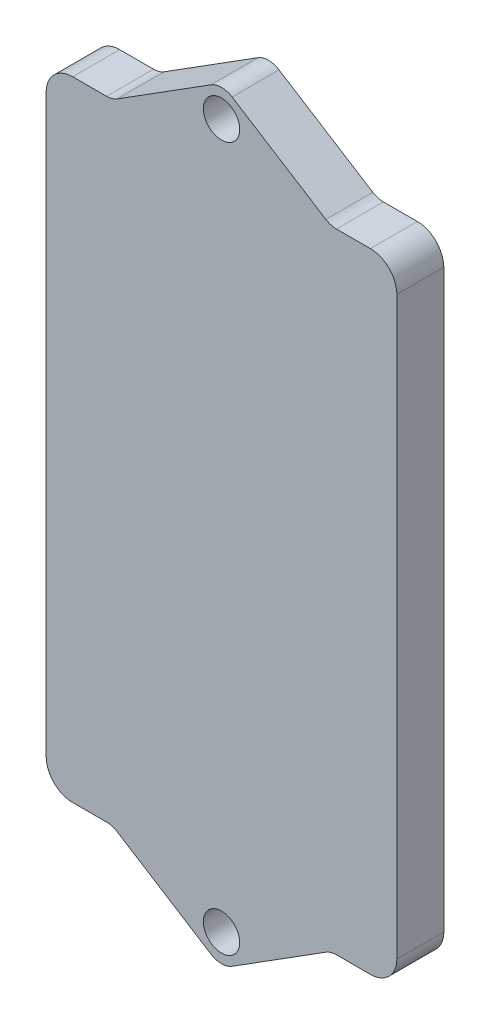
SolidWorks part; units mm, degrees
ref_plane "Plan de face" through (0, 0, 0) normal (0, 0, 1) x (1, 0, 0)
ref_plane "Plan de dessus" through (0, 0, 0) normal (0, 1, 0) x (1, 0, 0)
ref_plane "Plan de droite" through (0, 0, 0) normal (1, 0, 0) x (0, 0, -1)
sketch "Esquisse1" plane through (0, 0, 0) normal (0, 0, 1) x (1, 0, 0)
  line L0 (10, 95) -> (26.5, 105.4)
  line L1 (0, 0) -> (10, 0)
  line L2 (0, 0) -> (0, 95)
  line L3 (0, 95) -> (10, 95)
  line L4 (53, 0) -> (53, 95)
  line L5 (26.5, 105.4) -> (43, 95)
  line L7 (10, 0) -> (26.5, -10.4)
  line L8 (26.5, -10.4) -> (43, 0)
  line L9 (43, 95) -> (53, 95)
  line L10 (43, 0) -> (53, 0)
  circle A0 centre (26.5, 100.71) radius 2.75
  circle A1 centre (26.5, -5.71) radius 2.75
  point P16 (5, 0)
  dimension "D9" = 5.5
  dimension "D10" = 5.5
  dimension "D1" = 53
  dimension "D2" = 95
  dimension "D3" = 10
  dimension "D4" = 10
  dimension "D5" = 10.4
  dimension "D6" = 10.4
  dimension "D7" = 26.5
  dimension "D8" = 26.5
  dimension "D11" = 5.71
  dimension "D12" = 5.71
extrude "Boss.-Extru.1" add sketch "Esquisse1" along normal blind 7.1
fillet "Congé1" radius 3 6 edges at (43, 0, 3.55) (10, 0, 3.55) (10, 95, 3.55) (43, 95, 3.55) (26.5, -10.4, 3.55) (26.5, 105.4, 3.55)
fillet "Congé2" radius 4 4 edges at (0, 95, 3.55) (53, 95, 3.55) (53, 0, 3.55) (0, 0, 3.55)
sketch "Esquisse2" plane through (0, 0, 7.1) normal (0, 0, 1) x (1, 0, 0)
  line L0 (26.5, -8.46) -> (26.5, 103.46) construction
  circle A0 centre (26.5, -5.71) radius 2.75 construction
  circle A1 centre (26.5, 100.71) radius 2.75 construction
sketch "Esquisse3" plane through (0, 0, 0) normal (0, -1, 0) x (1, 0, 0)
  line L0 (5.1547, 0) -> (4, 2)
  line L1 (4, 0) -> (9.1334, 0) construction
  line L3 (10.1455, 2.0625) -> (8.9547, 0)
  line L4 (8.9547, 0) -> (5.1547, 0)
  line L5 (44.0092, 0) -> (42.8545, 2)
  line L6 (43.8666, 0) -> (49, 0) construction
  line L8 (49, 2.0625) -> (47.8092, 0)
  line L9 (47.8092, 0) -> (44.0092, 0)
  line L10 (4, 7.1) -> (4, 0) construction
  line L12 (4, 2) -> (4, 2.6625)
  line L13 (4, 2.6625) -> (10.1455, 2.6625)
  line L14 (10.1455, 2.0625) -> (10.1455, 2.6625)
  line L16 (42.8545, 2) -> (42.8545, 2.6625)
  line L17 (42.8545, 2.6625) -> (49, 2.6625)
  line L18 (49, 2.0625) -> (49, 2.6625)
  line L19 (49, 0) -> (49, 7.1) construction
  dimension "D1" = 60
  dimension "D2" = 60
  dimension "D3" = 3.8
  dimension "D4" = 3.8
  dimension "D5" = 2
  dimension "D6" = 2
  dimension "D7" = 0.6
  dimension "D8" = 0.6
extrude "Enlèv. mat.-Extru.1" cut sketch "Esquisse3" against normal blind 78 and the other way through all
fillet "Congé3" radius 0.3 4 edges at (44.0092, 39, 0) (47.8092, 39, 0) (8.9547, 39, 0) (5.1547, 39, 0)
